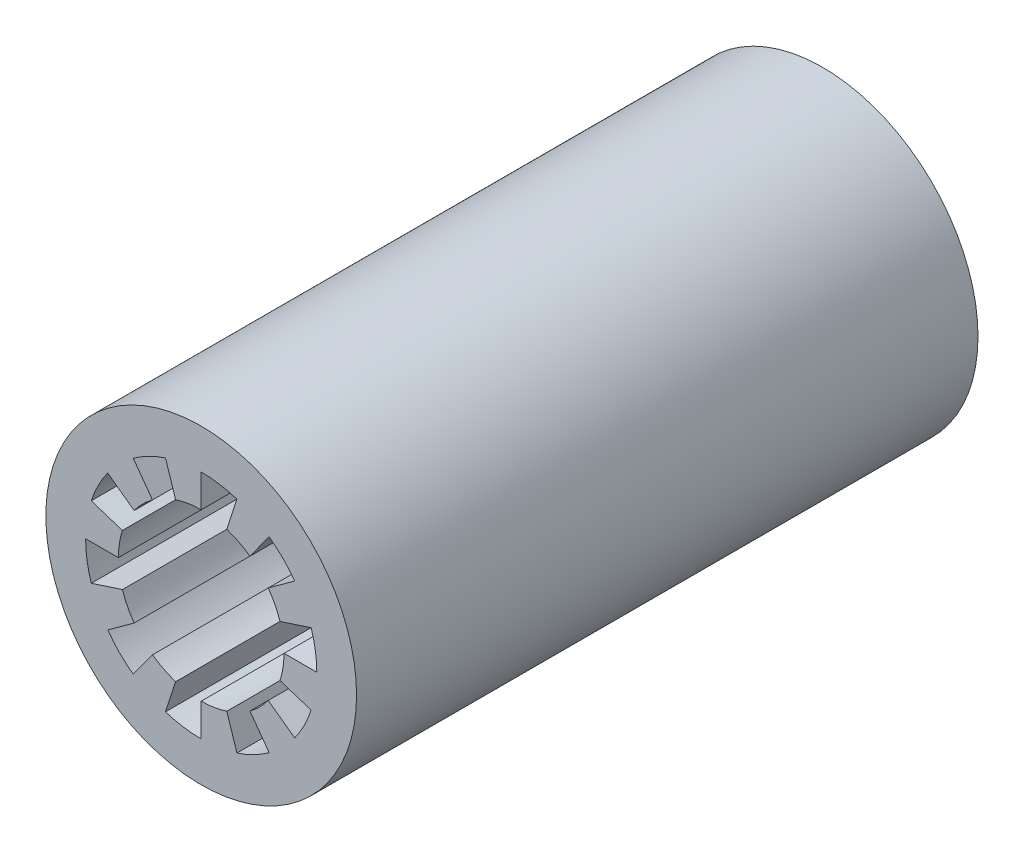
SolidWorks part; units mm, degrees
ref_plane "Front" through (0, 0, 0) normal (0, 0, 1) x (1, 0, 0)
ref_plane "Top" through (0, 0, 0) normal (0, 1, 0) x (1, 0, 0)
ref_plane "Right" through (0, 0, 0) normal (1, 0, 0) x (0, 0, -1)
sketch "Эскиз1" plane through (0, 0, 0) normal (0, 0, 1) x (1, 0, 0)
  point P0 (0, 0)
  line B0 (0, 5.58) -> (0, 4)
  line B1 (1.7243, 5.3069) -> (1.2361, 3.8042)
  line B2 (3.2798, 4.5143) -> (2.3511, 3.2361)
  line B3 (4.5143, 3.2798) -> (3.2361, 2.3511)
  line B4 (5.3069, 1.7243) -> (3.8042, 1.2361)
  line B5 (5.58, 0) -> (4, 0)
  line B6 (5.3069, -1.7243) -> (3.8042, -1.2361)
  line B7 (4.5143, -3.2798) -> (3.2361, -2.3511)
  line B8 (3.2798, -4.5143) -> (2.3511, -3.2361)
  line B9 (1.7243, -5.3069) -> (1.2361, -3.8042)
  line B10 (0, -5.58) -> (0, -4)
  line B11 (-1.7243, -5.3069) -> (-1.2361, -3.8042)
  line B12 (-3.2798, -4.5143) -> (-2.3511, -3.2361)
  line B13 (-4.5143, -3.2798) -> (-3.2361, -2.3511)
  line B14 (-5.3069, -1.7243) -> (-3.8042, -1.2361)
  line B15 (-5.58, 0) -> (-4, 0)
  line B16 (-5.3069, 1.7243) -> (-3.8042, 1.2361)
  line B17 (-4.5143, 3.2798) -> (-3.2361, 2.3511)
  line B18 (-3.2798, 4.5143) -> (-2.3511, 3.2361)
  line B19 (-1.7243, 5.3069) -> (-1.2361, 3.8042)
  arc B20 (0, 4) -> (-1.2361, 3.8042) centre (0, 0) ccw
  arc B21 (-4.5143, 3.2798) -> (-5.3069, 1.7243) centre (0, 0) ccw
  circle B22 centre (0, 0) radius 7.5
  arc B23 (2.3511, 3.2361) -> (1.2361, 3.8042) centre (0, 0) ccw
  arc B24 (3.8042, 1.2361) -> (3.2361, 2.3511) centre (0, 0) ccw
  arc B25 (3.8042, -1.2361) -> (4, 0) centre (0, 0) ccw
  arc B26 (2.3511, -3.2361) -> (3.2361, -2.3511) centre (0, 0) ccw
  arc B27 (0, -4) -> (1.2361, -3.8042) centre (0, 0) ccw
  arc B28 (-2.3511, -3.2361) -> (-1.2361, -3.8042) centre (0, 0) ccw
  arc B29 (-3.8042, -1.2361) -> (-3.2361, -2.3511) centre (0, 0) ccw
  arc B30 (-3.8042, 1.2361) -> (-4, 0) centre (0, 0) ccw
  arc B31 (-2.3511, 3.2361) -> (-3.2361, 2.3511) centre (0, 0) ccw
  arc B32 (-1.7243, 5.3069) -> (-3.2798, 4.5143) centre (0, 0) ccw
  arc B33 (1.7243, 5.3069) -> (0, 5.58) centre (0, 0) ccw
  arc B34 (4.5143, 3.2798) -> (3.2798, 4.5143) centre (0, 0) ccw
  arc B35 (5.58, 0) -> (5.3069, 1.7243) centre (0, 0) ccw
  arc B36 (4.5143, -3.2798) -> (5.3069, -1.7243) centre (0, 0) ccw
  arc B37 (1.7243, -5.3069) -> (3.2798, -4.5143) centre (0, 0) ccw
  arc B38 (-1.7243, -5.3069) -> (0, -5.58) centre (0, 0) ccw
  arc B39 (-4.5143, -3.2798) -> (-3.2798, -4.5143) centre (0, 0) ccw
  arc B40 (-5.58, 0) -> (-5.3069, -1.7243) centre (0, 0) ccw
sketch_block_instance "Блок1-1"
sketch_block "Блок1" parameters "D1"=5.6
extrude "Бобышка-Вытянуть1" add sketch "Эскиз1" along normal blind 30
